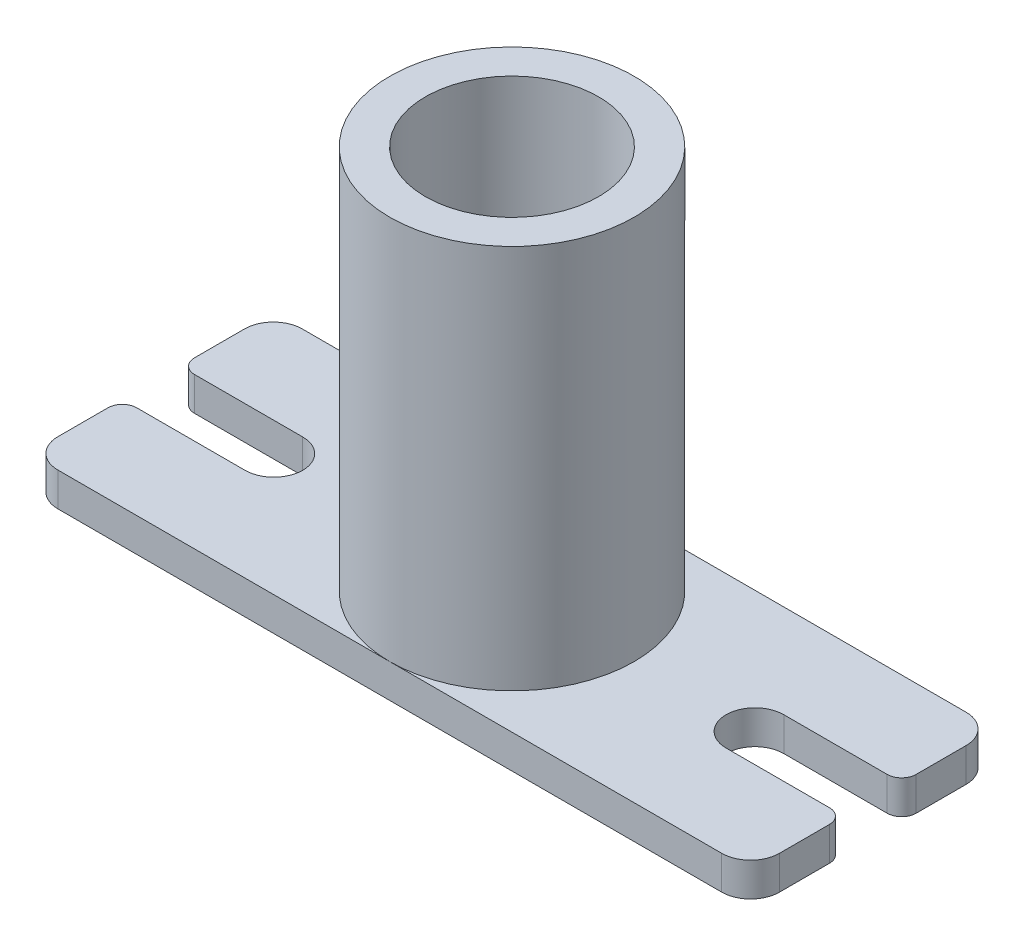
SolidWorks part; units mm, degrees
ref_plane "Front Plane" through (0, 0, 0) normal (0, 0, 1) x (1, 0, 0)
ref_plane "Top Plane" through (0, 0, 0) normal (0, 1, 0) x (1, 0, 0)
ref_plane "Right Plane" through (0, 0, 0) normal (1, 0, 0) x (0, 0, -1)
sketch "Sketch1" plane through (0, 0, 0) normal (0, 1, 0) x (1, 0, 0)
  line L0 (64.4531, 11.1008) -> (75.2031, 11.1008)
  line L1 (4.7031, 20.8008) -> (73.7031, 20.8008)
  line L2 (1.7031, 17.8008) -> (1.7031, 12.6008)
  line L3 (4.7031, -4.5992) -> (73.7031, -4.5992)
  line L4 (76.7031, 17.8008) -> (76.7031, 12.6008)
  line L5 (64.4531, 5.1008) -> (75.2031, 5.1008)
  line L6 (14.4531, 11.1008) -> (3.2031, 11.1008)
  line L7 (14.4531, 5.1008) -> (3.2031, 5.1008)
  line L8 (1.7031, 3.6008) -> (1.7031, -1.5992)
  line L9 (76.7031, 3.6008) -> (76.7031, -1.5992)
  arc A0 (14.4531, 5.1008) -> (14.4531, 11.1008) centre (14.4531, 8.1008) ccw
  arc A1 (64.4531, 11.1008) -> (64.4531, 5.1008) centre (64.4531, 8.1008) ccw
  arc A2 (3.2031, 5.1008) -> (1.7031, 3.6008) centre (3.2031, 3.6008) ccw
  arc A3 (3.2031, 11.1008) -> (1.7031, 12.6008) centre (3.2031, 12.6008) cw
  arc A4 (75.2031, 5.1008) -> (76.7031, 3.6008) centre (75.2031, 3.6008) cw
  arc A5 (75.2031, 11.1008) -> (76.7031, 12.6008) centre (75.2031, 12.6008) ccw
  arc A6 (73.7031, -4.5992) -> (76.7031, -1.5992) centre (73.7031, -1.5992) ccw
  arc A7 (73.7031, 20.8008) -> (76.7031, 17.8008) centre (73.7031, 17.8008) cw
  arc A8 (4.7031, -4.5992) -> (1.7031, -1.5992) centre (4.7031, -1.5992) cw
  arc A9 (4.7031, 20.8008) -> (1.7031, 17.8008) centre (4.7031, 17.8008) ccw
  point P16 (1.7031, 5.1008)
  point P21 (76.7031, 5.1008)
  point P26 (76.7031, -4.5992)
  point P29 (76.7031, 20.8008)
  point P34 (1.7031, 20.8008)
  dimension "D3" = 12.7
  dimension "D5" = 50
  dimension "D6" = 1.5
  dimension "D7" = 3
  dimension "D1" = 75
  dimension "D2" = 25.4
  dimension "D4" = 12.75
extrude "Boss-Extrude2" add sketch "Sketch1" along normal blind 3.5
sketch "Sketch4" plane through (0, 3.5, 0) normal (0, 1, 0) x (1, 0, 0)
  line L0 (76.7031, -1.5992) -> (76.7031, 3.6008) construction
  circle A0 centre (39.2031, 8.1008) radius 12.7
  dimension "D1" = 37.5
extrude "Boss-Extrude3" add sketch "Sketch4" along normal blind 15
sketch "Sketch5" plane through (0, 18.5, 0) normal (0, 1, 0) x (1, 0, 0)
  circle A0 centre (39.2031, 8.1008) radius 9
  circle A1 centre (39.2031, 8.1008) radius 12.7 construction
  circle A2 centre (39.2031, 8.1008) radius 12.7
  dimension "D1" = 0
extrude "Boss-Extrude4" add sketch "Sketch5" along normal blind 25
